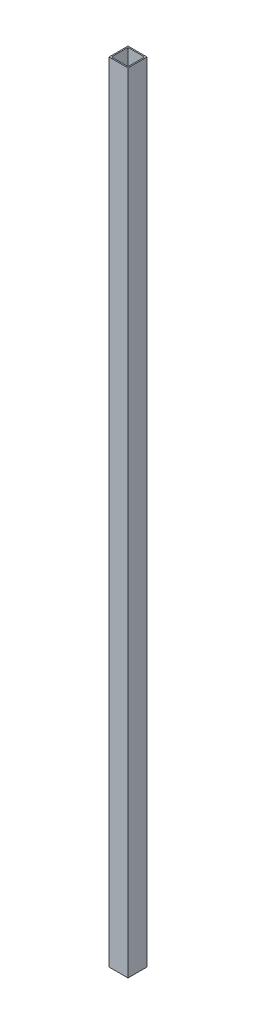
SolidWorks part; units mm, degrees
material "6061 Alloy"
ref_plane "Front Plane" through (0, 0, 0) normal (0, 0, 1) x (1, 0, 0)
ref_plane "Top Plane" through (0, 0, 0) normal (0, 1, 0) x (1, 0, 0)
ref_plane "Right Plane" through (0, 0, 0) normal (1, 0, 0) x (0, 0, -1)
sketch "Sketch1" plane through (0, 0, 0) normal (0, 1, 0) x (1, 0, 0)
  line L1 (-12.7, -12.7) -> (12.7, -12.7)
  line L2 (-12.7, -12.7) -> (-12.7, 12.7)
  line L3 (-12.7, 12.7) -> (12.7, 12.7)
  line L4 (12.7, -12.7) -> (12.7, 12.7)
  line L7 (-11.1125, -11.1125) -> (11.1125, -11.1125)
  line L8 (-11.1125, -11.1125) -> (-11.1125, 11.1125)
  line L9 (-11.1125, 11.1125) -> (11.1125, 11.1125)
  line L10 (11.1125, -11.1125) -> (11.1125, 11.1125)
  point P6 (0, 0)
  dimension "D1" = 25.4
  dimension "D2" = 25.4
  dimension "D3" = 1.5875
  dimension "D4" = 1.5875
  dimension "D5" = 1.5875
extrude "Boss-Extrude1" add sketch "Sketch1" along normal blind 1054.1
